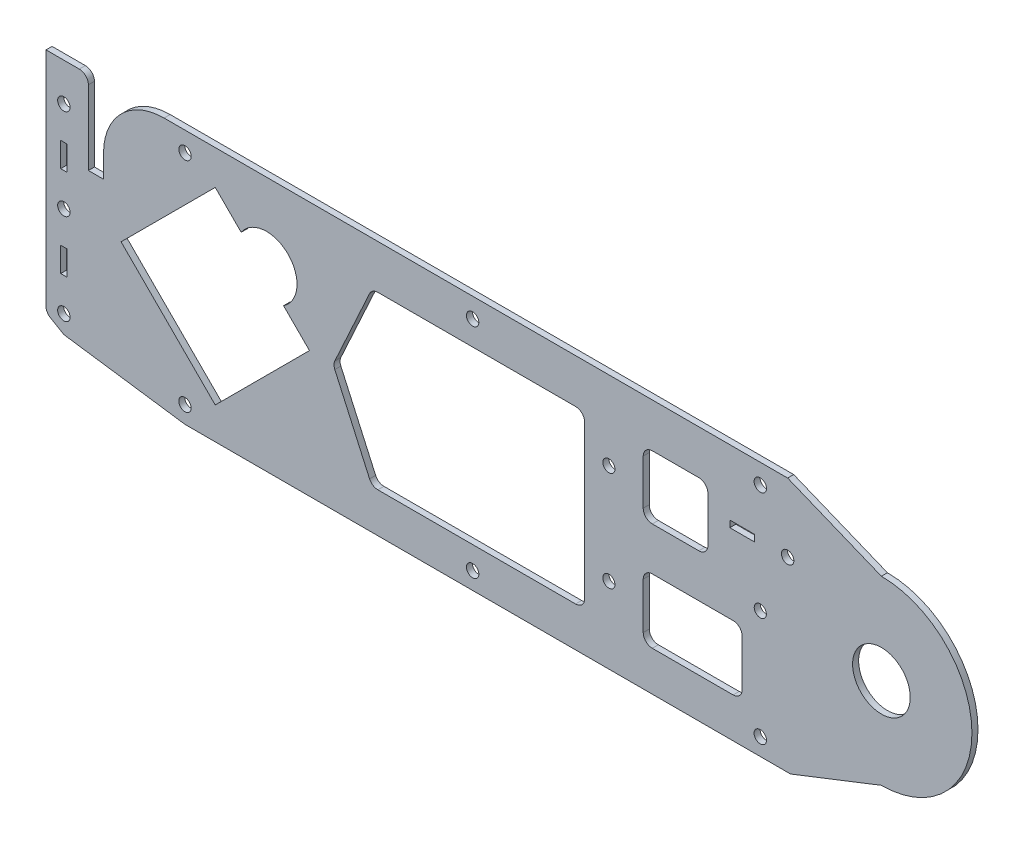
SolidWorks part; units mm, degrees
ref_plane "前视基准面" through (0, 0, 0) normal (0, 0, 1) x (1, 0, 0)
ref_plane "上视基准面" through (0, 0, 0) normal (0, 1, 0) x (1, 0, 0)
ref_plane "右视基准面" through (0, 0, 0) normal (1, 0, 0) x (0, 0, -1)
sketch "草图1" plane through (0, 0, 0) normal (0, 0, 1) x (1, 0, 0)
  line L0 (0.5429, 31.9043) -> (0.5429, 27.8043) construction
  line L1 (0.5429, 18.7543) -> (0.5429, 10.9543) construction
  line L2 (-0.5071, 10.8043) -> (1.5929, 10.8043)
  line L3 (-0.5071, 10.8043) -> (-0.5071, 18.9043)
  line L4 (-0.5071, 18.9043) -> (1.5929, 18.9043)
  line L5 (1.5929, 10.8043) -> (1.5929, 18.9043)
  line L6 (-0.5071, 10.8043) -> (1.5929, 18.9043) construction
  line L7 (-0.5071, 18.9043) -> (1.5929, 10.8043) construction
  line L12 (270.5429, -30.0457) -> (240.5429, -41.8157)
  line L18 (50.5429, -0.1457) -> (97.8433, -0.1457) construction
  line L19 (50.5429, -0.1457) -> (270.5429, -0.1457) construction
  line L20 (240.6429, -0.1457) -> (240.6429, 38.1043) construction
  line L62 (50.5429, 13.8543) -> (59.0992, 22.4106) construction
  line L63 (64.5429, -0.1457) -> (73.0992, 8.4106) construction
  line L64 (59.0992, 22.4106) -> (50.5429, 30.967)
  line L65 (19.4302, -0.1457) -> (50.5429, 30.967)
  line L66 (19.4302, -0.1457) -> (50.5429, -31.2584)
  line L67 (50.5429, -31.2584) -> (81.6556, -0.1457)
  line L68 (50.5429, 30.967) -> (81.6556, -0.1457) construction
  line L69 (19.4302, -0.1457) -> (81.6556, -0.1457) construction
  line L70 (50.5429, -31.2584) -> (50.5429, 30.967) construction
  line L71 (73.0992, 8.4106) -> (81.6556, -0.1457)
  line L72 (0.5429, -0.1457) -> (50.5429, -0.1457) construction
  line L73 (-0.5071, -19.1957) -> (1.5929, -11.0957) construction
  line L74 (-0.5071, -11.0957) -> (1.5929, -19.1957) construction
  line L75 (0.5429, -19.0457) -> (0.5429, -11.2457) construction
  line L76 (1.5929, -11.0957) -> (1.5929, -19.1957)
  line L77 (-0.5071, -19.1957) -> (1.5929, -19.1957)
  line L78 (-0.5071, -11.0957) -> (-0.5071, -19.1957)
  line L79 (-0.5071, -11.0957) -> (1.5929, -11.0957)
  line L96 (89.4646, -0.1457) -> (102.301, 27.8043)
  line L103 (239.574, 19.7043) -> (224.574, 19.7043) construction
  line L104 (228.674, 20.8043) -> (220.474, 20.8043)
  line L105 (228.674, 20.8043) -> (228.674, 18.6043)
  line L106 (228.674, 18.6043) -> (220.474, 18.6043)
  line L107 (220.474, 20.8043) -> (220.474, 18.6043)
  line L108 (228.674, 20.8043) -> (220.474, 18.6043) construction
  line L109 (228.674, 18.6043) -> (220.474, 20.8043) construction
  line L114 (270.5429, 29.7543) -> (239.574, 42.359)
  line L116 (102.301, 27.8043) -> (172.548, 27.8043)
  line L117 (172.548, 27.8043) -> (172.548, -28.6767)
  line L118 (172.548, -28.6767) -> (102.301, -28.6767)
  line L119 (102.301, -28.6767) -> (89.4646, -0.1457)
  line L120 (191.8783, 27.8043) -> (191.8783, 6.8862)
  line L121 (191.8783, 6.8862) -> (213.241, 6.8862)
  line L122 (213.241, 6.8862) -> (213.241, 27.8043)
  line L123 (213.241, 27.8043) -> (191.8783, 27.8043)
  line L126 (213.241, -28.6767) -> (191.8783, -28.6767)
  line L127 (191.8783, -28.6767) -> (191.8783, -7.4155)
  line L128 (191.8783, -7.4155) -> (224.574, -7.4155)
  line L129 (224.574, -7.4155) -> (224.574, -28.6767)
  line L130 (224.574, -28.6767) -> (213.241, -28.6767)
  line L131 (-5.3571, 42.359) -> (8.6429, 42.359)
  line L136 (8.6429, 42.359) -> (8.6429, 14.8543)
  line L137 (8.6429, 14.8543) -> (13.6429, 14.8543)
  line L138 (13.6429, 14.8543) -> (13.6429, 42.359)
  line L139 (13.6429, 42.359) -> (239.574, 42.359)
  line L140 (240.5429, -41.8157) -> (40.5429, -41.8157)
  line L141 (40.5429, -41.8157) -> (0.5429, -36.1457)
  line L142 (0.5429, -36.1457) -> (-5.3571, -32.6892)
  line L143 (-5.3571, -32.6892) -> (-5.3571, 42.359)
  circle A0 centre (0.5429, 29.8543) radius 2.05
  circle A1 centre (0.5429, -0.1457) radius 2.05
  circle A2 centre (0.5429, -30.1457) radius 2.05
  circle A15 centre (270.5429, -0.1457) radius 9.525
  circle A16 centre (270.5429, -0.1457) radius 29.9 construction
  arc A17 (270.5429, -30.0457) -> (270.5429, 29.7543) centre (270.5429, -0.1457) ccw
  arc A19 (59.0992, 22.4106) -> (73.0992, 8.4106) centre (67.4545, 16.7659) cw
  circle A25 centre (230.5429, -0.1457) radius 2
  circle A26 centre (180.5429, 16.3543) radius 2
  circle A27 centre (180.5429, -16.6457) radius 2
  circle A28 centre (270.5429, -0.1457) radius 2 construction
  circle A29 centre (239.574, 19.7043) radius 2.05
  circle A30 centre (40.5429, -36.1457) radius 2.05
  circle A31 centre (135.5429, -36.1457) radius 2.05
  circle A32 centre (230.5429, -36.1457) radius 2.05
  circle A33 centre (135.5429, 35.8543) radius 2.05
  circle A34 centre (230.5429, 35.8543) radius 2.05
  circle A35 centre (40.5429, 35.8543) radius 2.05
  point P6 (0.5429, 14.8543)
  point P25 (50.5429, -0.1457)
  point P67 (0.5429, -15.1457)
  point P106 (0.5429, -0.1457)
  dimension "D3" = 44
  dimension "D4" = 44
  dimension "D10" = 2.2
  dimension "D13" = 19.05
  dimension "D12" = 6
  dimension "D6" = 15
  dimension "D8" = 40
  dimension "D1" = 8.1
  dimension "D2" = 2.1
  dimension "D5" = 50
  dimension "D7" = 15
  dimension "D9" = 30
  dimension "D11" = 8.2
  dimension "D14" = 220
  dimension "D17" = 8.1
  dimension "D15" = 3
  dimension "D16" = 2
extrude "凸台-拉伸1" add sketch "草图1" along normal blind 2
fillet "圆角1" radius 3 13 edges at (172.548, -28.6767, 1) (172.548, 27.8043, 1) (224.574, -28.6767, 1) (213.241, 6.8862, 1) (224.574, -7.4155, 1) (213.241, 27.8043, 1) (191.8783, -7.4155, 1) (191.8783, 27.8043, 1) (102.301, 27.8043, 1) (191.8783, 6.8862, 1) (191.8783, -28.6767, 1) (89.4646, -0.1457, 1) (102.301, -28.6767, 1)
fillet "圆角2" radius 20 1 edges at (13.6429, 42.359, 1)
fillet "圆角4" radius 3 4 edges at (8.6429, 42.359, 1) (40.5429, -41.8157, 1) (0.5429, -36.1457, 1) (-5.3571, -32.6892, 1)
